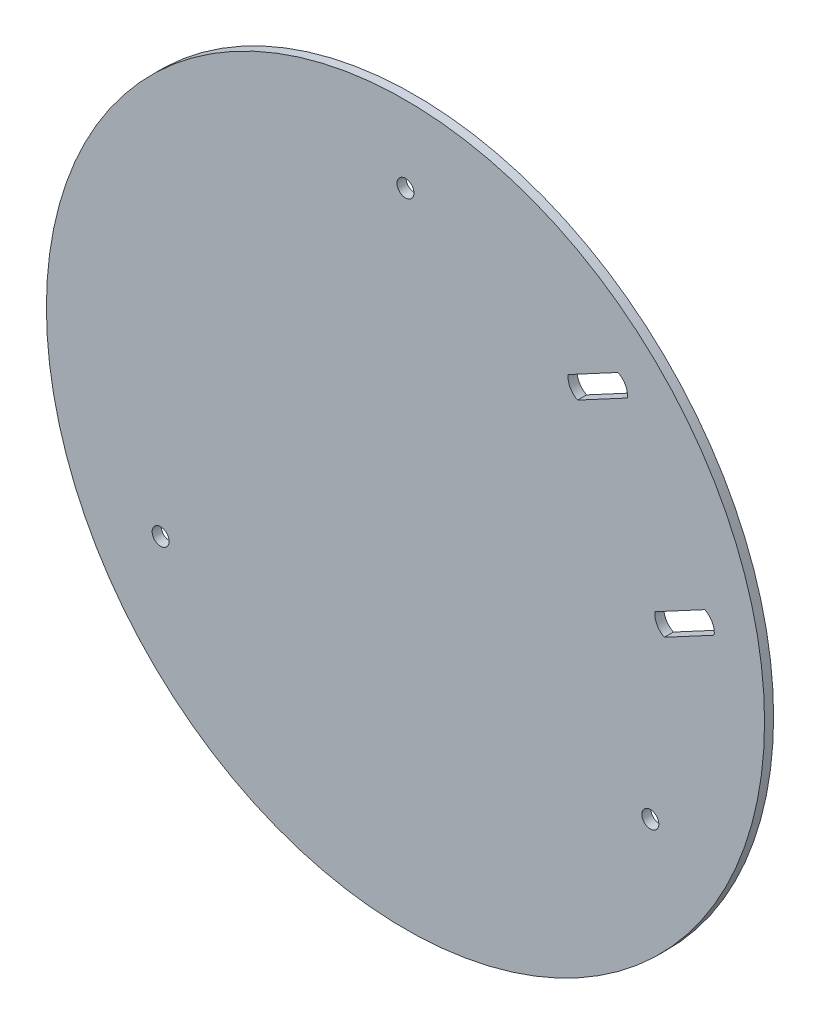
SolidWorks part; units mm, degrees
ref_plane "Front Plane" through (0, 0, 0) normal (0, 0, 1) x (1, 0, 0)
ref_plane "Top Plane" through (0, 0, 0) normal (0, 1, 0) x (1, 0, 0)
ref_plane "Right Plane" through (0, 0, 0) normal (1, 0, 0) x (0, 0, -1)
sketch "Sketch1" plane through (0, 0, 0) normal (0, 0, 1) x (1, 0, 0)
  circle A0 centre (0, 0) radius 63.5
  dimension "D1" = 127
extrude "Boss-Extrude1" add sketch "Sketch1" along normal blind 1.6
sketch "Sketch2" plane through (0, 0, 0) normal (0, 0, -1) x (-1, 0, 0)
  circle A0 centre (0, 0) radius 50
  circle A1 centre (0, 50) radius 1.5
  circle A2 centre (43.3013, -25) radius 1.5
  circle A3 centre (-43.3013, -25) radius 1.5
  point P11 (0, 0)
  dimension "D1" = 100
  dimension "D2" = 3
  dimension "D3" = 3
sketch "Sketch3" plane through (0, 0, 0) normal (0, 0, -1) x (-1, 0, 0)
  circle A0 centre (-34.0063, 36.6548) radius 1.75
  circle A1 centre (-49.3547, 8.0073) radius 1.75
  circle A2 centre (0, 0) radius 63.5 construction
  dimension "D1" = 3.5
  dimension "D2" = 3.5
  dimension "D3" = 32.5
  dimension "D4" = 50
  dimension "D5" = 50
extrude "Cut-Extrude4" cut sketch "Sketch3" against normal blind 1.6
extrude "Cut-Extrude5" cut sketch "Sketch2" against normal blind 1.6 contours A1 | A3 | A2
sketch "Sketch4" plane through (0, 0, 0) normal (0, 0, -1) x (-1, 0, 0)
  line L0 (-34.8328, 35.1122) -> (-48.5282, 9.5498) construction
  line L2 (-52.9355, 11.9111) -> (-44.1209, 7.1886)
  line L3 (-54.5884, 8.826) -> (-45.7738, 4.1034)
  line L6 (-39.2401, 37.4735) -> (-30.4255, 32.7509)
  line L7 (-37.5872, 40.5586) -> (-28.7726, 35.836)
  arc A1 (-45.7738, 4.1034) -> (-44.1209, 7.1886) centre (-47.151, 6.8266) ccw
  circle A2 centre (-34.0063, 36.6548) radius 1.75 construction
  arc A3 (-30.4255, 32.7509) -> (-28.7726, 35.836) centre (-31.8027, 35.4741) ccw
  arc A4 (-39.2401, 37.4735) -> (-37.5872, 40.5586) centre (-36.21, 37.8354) cw
  arc A5 (-54.5884, 8.826) -> (-52.9355, 11.9111) centre (-51.5583, 9.1879) cw
  dimension "D3" = 5
extrude "Cut-Extrude6" cut sketch "Sketch4" against normal blind 10 contours L2 A1 L3 A5 | L6 A3 L7 A4
